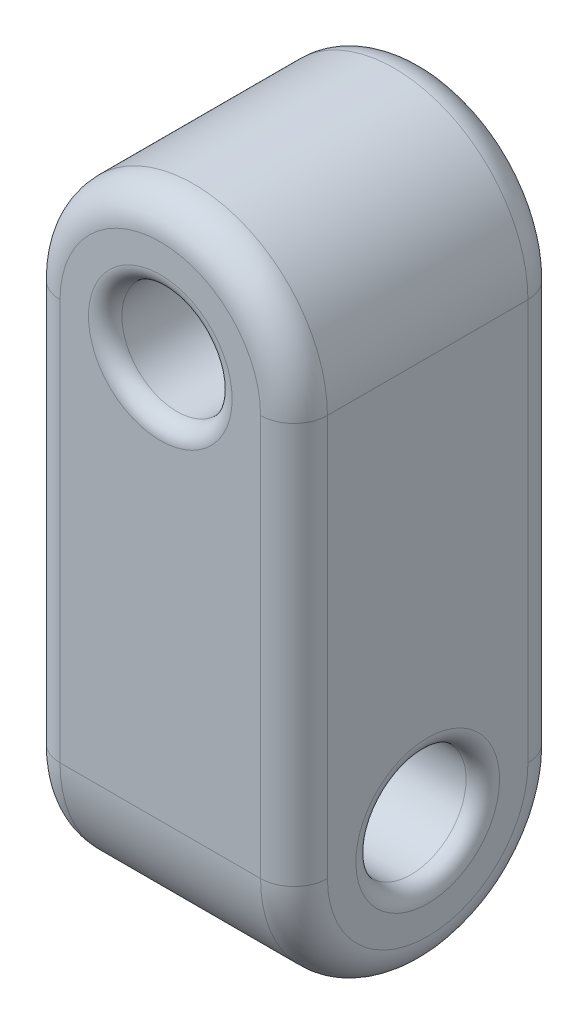
SolidWorks part; units mm, degrees
ref_plane "Front Plane" through (0, 0, 0) normal (0, 0, 1) x (1, 0, 0)
ref_plane "Top Plane" through (0, 0, 0) normal (0, 1, 0) x (1, 0, 0)
ref_plane "Right Plane" through (0, 0, 0) normal (1, 0, 0) x (0, 0, -1)
sketch "Sketch1" plane through (0, 0, 0) normal (0, 0, 1) x (1, 0, 0)
  circle A0 centre (0, 0) radius 1.65
sketch "Sketch2" plane through (0, 0, 0) normal (0, 0, 1) x (1, 0, 0)
  circle A0 centre (0, 0) radius 4
extrude "Boss-Extrude1" add sketch "Sketch2" along normal blind 8 from offset 0.8
sketch "Sketch7" plane through (0, 0, 0.8) normal (0, 0, -1) x (-1, 0, 0)
  line L0 (0, 0) -> (0, -18) construction
  dimension "D1" = 18
sketch "Sketch8" plane through (0, 0, 0) normal (1, 0, 0) x (0, 0, -1)
  circle A0 centre (-4.8, -12) radius 4
  dimension "D1" = 12
sketch "Sketch9" plane through (0, 0, 0) normal (1, 0, 0) x (0, 0, -1)
  circle A0 centre (-4.8, -12) radius 1.65
  dimension "D1" = 12
sketch "Sketch10" plane through (0, 0, 0.8) normal (0, 0, -1) x (-1, 0, 0)
  line L1 (-4, 0) -> (4, 0)
  line L2 (-4, 0) -> (-4, -12)
  line L3 (-4, -12) -> (4, -12)
  line L4 (4, 0) -> (4, -12)
  circle A0 centre (0, 0) radius 4 construction
  dimension "D1" = 12
extrude "Boss-Extrude2" add sketch "Sketch10" against normal blind 8 contours L4 L3 L2 L1
extrude "Boss-Extrude3" add sketch "Sketch8" against normal blind 8 from offset 4 contours A0
extrude "Cut-Extrude2" cut sketch "Sketch1" along normal blind 9.6 contours A0
extrude "Cut-Extrude3" cut sketch "Sketch9" against normal blind 9.95 from offset 4.975
fillet "Fillet1" radius 1 8 edges at (4, -6, 8.8) (4, -6, 0.8) (4, -16, 4.8) (-4, -6, 0.8) (-4, -6, 8.8) (-4, -16, 4.8) (0, 4, 8.8) (0, 4, 0.8)
fillet "Fillet2" radius 0.5 4 edges at (1.65, 0, 8.8) (1.65, 0, 0.8) (-4, -12, 3.15) (4, -10.35, 4.8)
